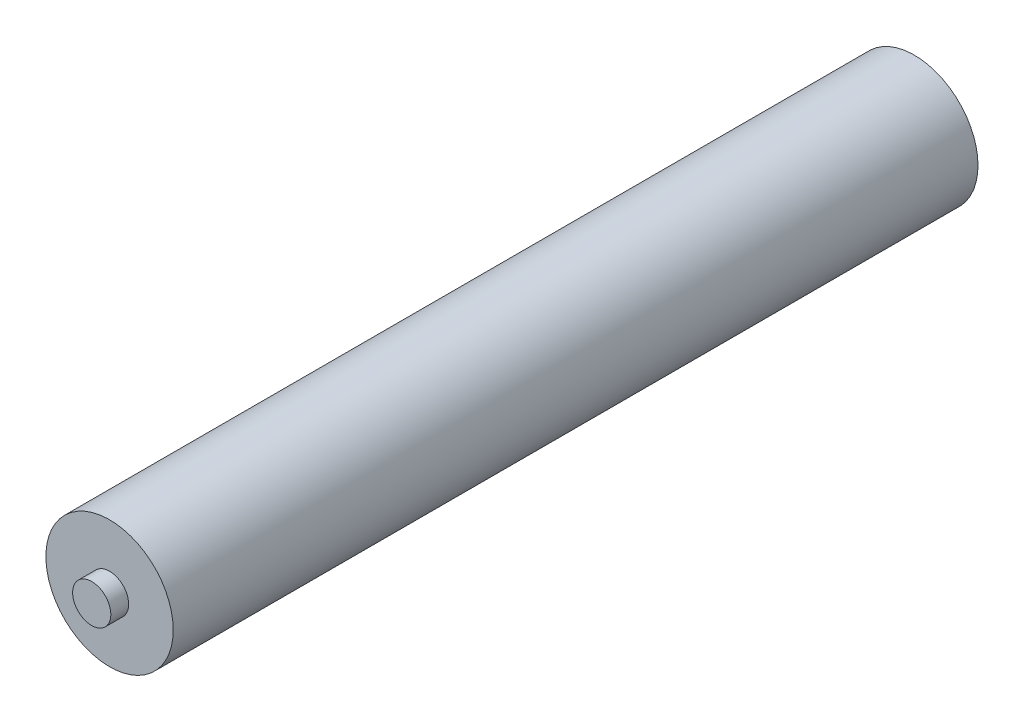
SolidWorks part; units mm, degrees
ref_plane "Front Plane" through (0, 0, 0) normal (0, 0, 1) x (1, 0, 0)
ref_plane "Top Plane" through (0, 0, 0) normal (0, 1, 0) x (1, 0, 0)
ref_plane "Right Plane" through (0, 0, 0) normal (1, 0, 0) x (0, 0, -1)
sketch "Sketch1" plane through (0, 0, 0) normal (0, 0, 1) x (1, 0, 0)
  circle A0 centre (0, 0) radius 12.5
  dimension "D1" = 25
extrude "Boss-Extrude1" add sketch "Sketch1" along normal mid plane 158
sketch "Sketch2" plane through (0, 0, 79) normal (0, 0, 1) x (1, 0, 0)
  circle A0 centre (0, 0) radius 3.75
  dimension "D1" = 7.5
extrude "Boss-Extrude2" add sketch "Sketch2" along normal mid plane 7
mirror "Mirror1" about plane through (0, 0, 0) normal (0, 0, 1) of "Boss-Extrude2"
